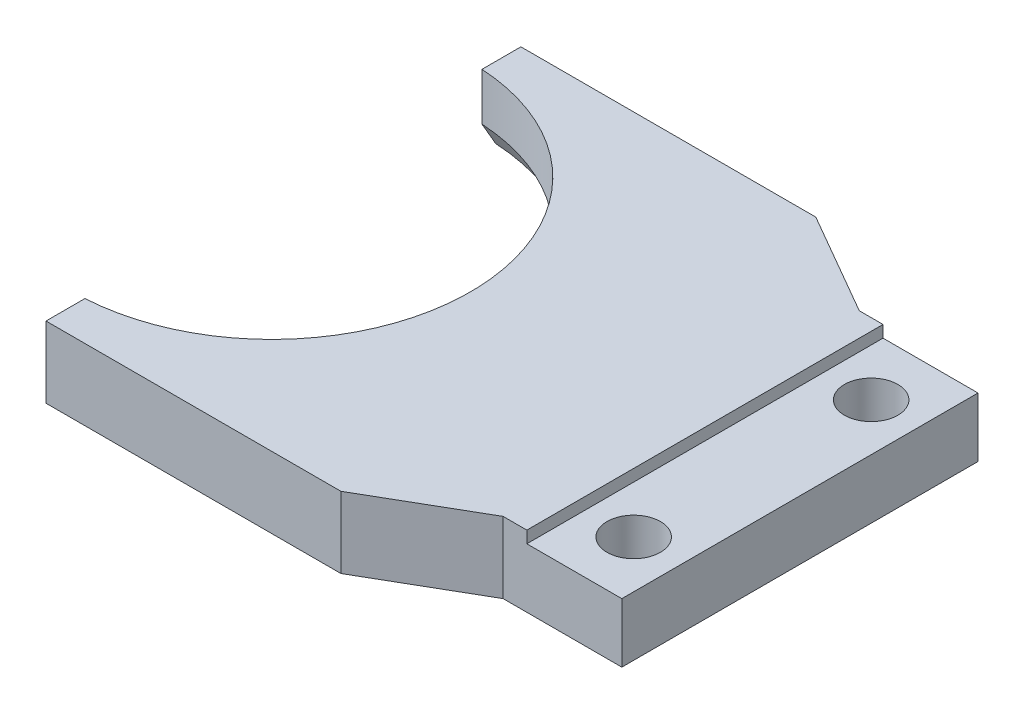
SolidWorks part; units mm, degrees
ref_plane "Alzado" through (0, 0, 0) normal (0, 0, 1) x (1, 0, 0)
ref_plane "Planta" through (0, 0, 0) normal (0, 1, 0) x (1, 0, 0)
ref_plane "Vista lateral" through (0, 0, 0) normal (1, 0, 0) x (0, 0, -1)
sketch "Croquis1" plane through (0, 0, 0) normal (0, 1, 0) x (1, 0, 0)
  line L0 (1, 20) -> (25.8397, 20)
  line L1 (25.8397, 20) -> (34.5, 15)
  line L2 (34.5, 15) -> (44.5, 15)
  line L3 (44.5, 15) -> (44.5, -15)
  line L4 (44.5, -15) -> (34.5, -15)
  line L5 (34.5, -15) -> (25.8397, -20)
  line L6 (25.8397, -20) -> (1, -20)
  line L7 (1, -20) -> (1, -16.7201)
  line L8 (1, 16.7201) -> (1, 20)
  arc A0 (1, -16.7201) -> (1, 16.7201) centre (0, 0) ccw
  circle A1 centre (40.5, 10) radius 2.25
  circle A2 centre (40.5, -10) radius 2.25
  dimension "D11" = 16.75
  dimension "D12" = 4
  dimension "D13" = 4
  dimension "D14" = 10
  dimension "D16" = 4.5
  dimension "D17" = 4.5
  dimension "D1" = 43.5
  dimension "D2" = 20
  dimension "D3" = 20
  dimension "D4" = 15
  dimension "D5" = 15
  dimension "D6" = 10
  dimension "D7" = 10
  dimension "D8" = 30
  dimension "D9" = 30
  dimension "D10" = 1
  dimension "D15" = 10
extrude "Saliente-Extruir2" add sketch "Croquis1" along normal blind 6 contours A0 L8 L0 L1 L2 L3 L4 L5 L6 L7
sketch "Croquis2" plane through (0, 6, 0) normal (0, 1, 0) x (1, 0, 0)
  line L0 (34.5, -15) -> (44.5, -15) construction
  line L1 (44.5, 15) -> (36.5, 15)
  line L2 (44.5, 15) -> (44.5, -15)
  line L3 (44.5, -15) -> (36.5, -15)
  line L4 (36.5, 15) -> (36.5, -15)
  dimension "D1" = 8
extrude "Cortar-Extruir1" cut sketch "Croquis2" against normal blind 1
sketch "Croquis3" plane through (0, 0, 0) normal (0, 0, 1) x (1, 0, 0)
  line L0 (16.75, 0) -> (16.75, 2)
  line L1 (1, 0) -> (16.75, 0) construction
  line L2 (16.75, 2) -> (17.9047, 0)
  line L3 (25.8397, 0) -> (1, 0) construction
  line L4 (17.9047, 0) -> (16.75, 0)
  dimension "D1" = 2
  dimension "D2" = 30
  dimension "D3" = 16.75
revolve "Cortar-Revolución1" cut sketch "Croquis3" angle 360 about axis through (0, 6, 0) along (0, -1, 0)
